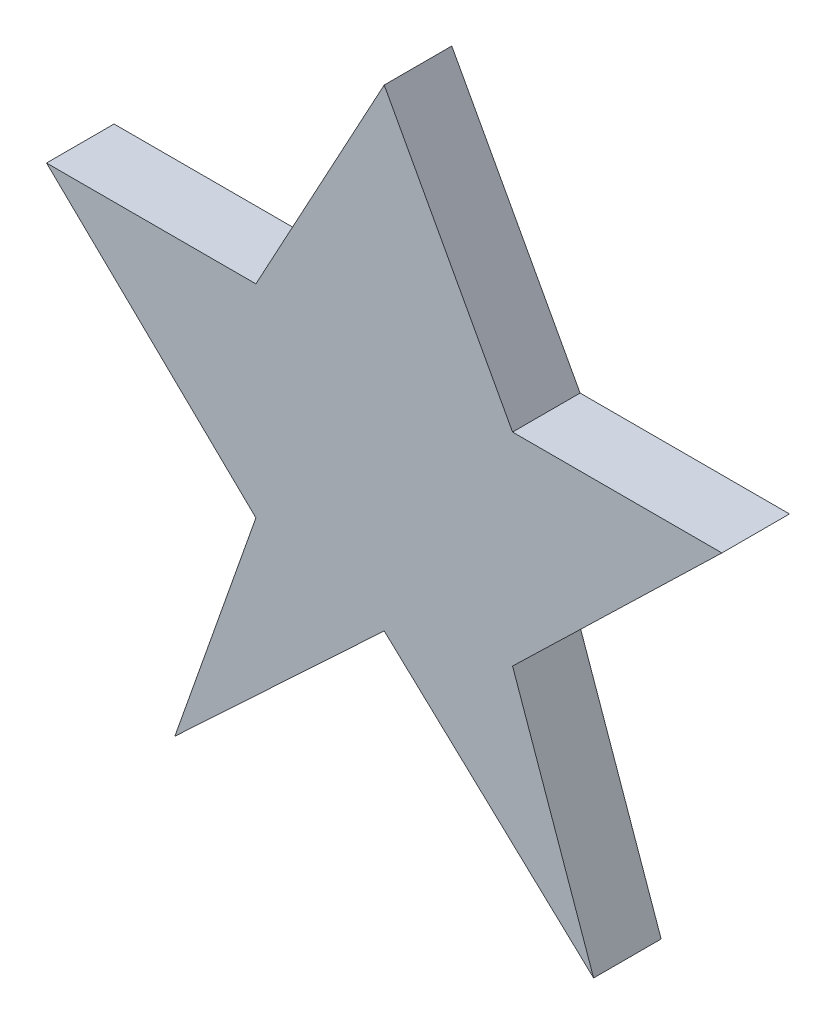
SolidWorks part; units mm, degrees
ref_plane "前视基准面" through (0, 0, 0) normal (0, 0, 1) x (1, 0, 0)
ref_plane "上视基准面" through (0, 0, 0) normal (0, 1, 0) x (1, 0, 0)
ref_plane "右视基准面" through (0, 0, 0) normal (1, 0, 0) x (0, 0, -1)
other "Configuration Table"
sketch "草图1" plane through (0, 0, 0) normal (0, 0, 1) x (1, 0, 0)
  line L0 (0, 500) -> (190, 150)
  line L1 (190, 150) -> (500, 150)
  line L2 (500, 150) -> (190, -150)
  line L3 (190, -150) -> (310, -490)
  line L4 (310, -490) -> (0, -200)
  line L5 (0, -200) -> (-310, -490)
  line L6 (-310, -490) -> (-190, -150)
  line L7 (-190, -150) -> (-500, 150)
  line L8 (-500, 150) -> (-190, 150)
  line L9 (-190, 150) -> (0, 500)
extrude "凸台-拉伸1" add sketch "草图1" along normal blind 100
